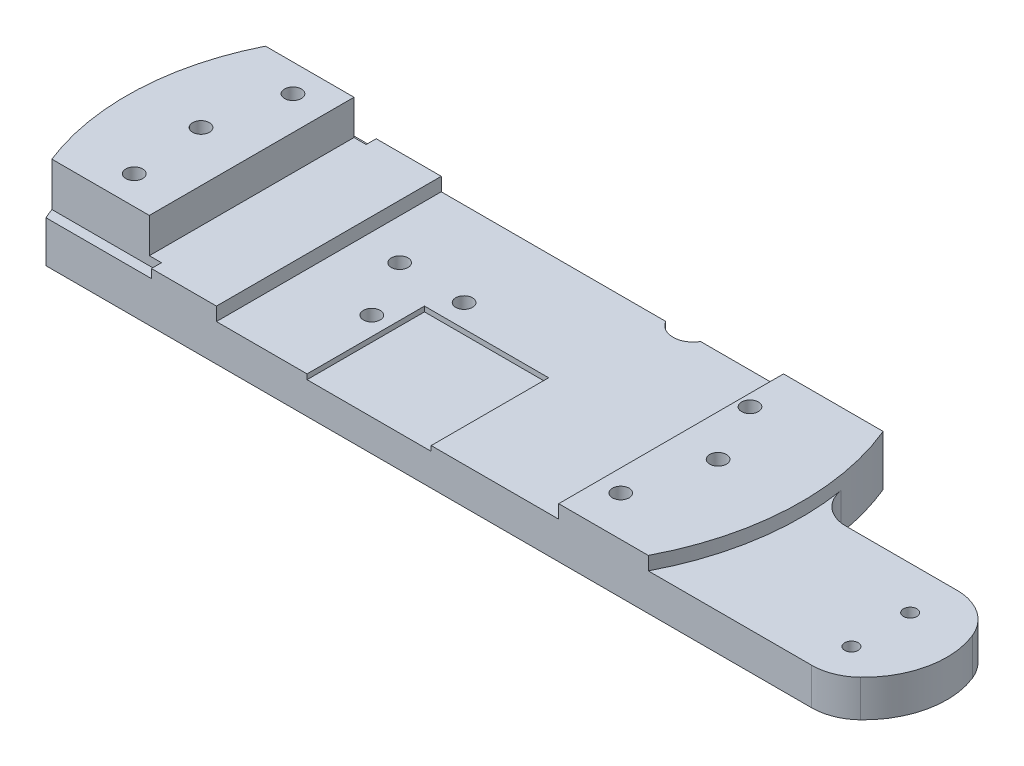
SolidWorks part; units mm, degrees
ref_plane "Front Plane" through (0, 0, 0) normal (0, 0, 1) x (1, 0, 0)
ref_plane "Top Plane" through (0, 0, 0) normal (0, 1, 0) x (1, 0, 0)
ref_plane "Right Plane" through (0, 0, 0) normal (1, 0, 0) x (0, 0, -1)
sketch "Sketch1" plane through (0, 0, 0) normal (0, 1, 0) x (1, 0, 0)
  line L1 (-97.5, -33.5) -> (97.5, -33.5)
  line L2 (-97.5, -33.5) -> (-97.5, 33.5)
  line L3 (-97.5, 33.5) -> (97.5, 33.5)
  line L4 (97.5, -33.5) -> (97.5, 33.5)
  line L5 (-97.5, -33.5) -> (97.5, 33.5) construction
  line L6 (-97.5, 33.5) -> (97.5, -33.5) construction
  point P0 (0, 0)
  dimension "D1" = 67
  dimension "D2" = 195
extrude "Boss-Extrude1" add sketch "Sketch1" along normal blind 25.4
sketch "Sketch2" plane through (0, 0, 0) normal (0, -1, 0) x (1, 0, 0)
  line L0 (-97.5, -33.5) -> (-97.5, 33.5) construction
  line L1 (97.5, 33.5) -> (97.5, -33.5) construction
  line L2 (97.5, 33.5) -> (88.5, 33.5)
  line L3 (-97.5, 33.5) -> (97.5, 33.5) construction
  line L4 (97.5, -33.5) -> (91.5, -33.5)
  line L5 (97.5, -33.5) -> (-97.5, -33.5) construction
  line L6 (-97.5, 33.5) -> (-91, 33.5)
  line L7 (-97.5, -33.5) -> (-88, -33.5)
  circle A0 centre (18.0922, -3.2198) radius 79.4078
  circle A1 centre (-22.6589, 2.9929) radius 74.8411
  line M7 (97.5, -33.5) -> (97.5, 33.5)
  line M8 (97.5, 33.5) -> (-97.5, 33.5)
  line M9 (-97.5, 33.5) -> (-97.5, -33.5)
  line M10 (-97.5, -33.5) -> (97.5, -33.5)
  dimension "D1" = 9
  dimension "D2" = 6
  dimension "D3" = 6.5
  dimension "D4" = 9.5
extrude "Cut-Extrude1" cut sketch "Sketch2" against normal through all contours A0 M7 M8 | A0 M10 M7 | A1 M9 M10 | A1 M8 M9
sketch "Sketch3" plane through (0, 0, 33.5) normal (0, 0, -1) x (-1, 0, 0)
  line L0 (97.5, 25.4) -> (63.2, 25.4)
  line L2 (63.2, 25.4) -> (63.2, 15)
  line L3 (63.2, 15) -> (40.2, 15)
  line L4 (40.2, 15) -> (40.2, 11)
  line L5 (40.2, 11) -> (-61.8, 11)
  line L6 (-91.5, 25.4) -> (88, 25.4) construction
  line L10 (97.5, 0) -> (97.5, 25.4) construction
  line L11 (-61.8, 11) -> (-61.8, 15)
  line L12 (-61.8, 15) -> (-97.5, 15)
  line L13 (-97.5, 25.4) -> (-97.5, 0) construction
  line L14 (-97.5, 15) -> (-97.5, 25.4)
  line L15 (-97.5, 25.4) -> (63.2, 25.4)
  line M13 (-88.5, 0) -> (-88.5, 25.4)
  line M14 (-88.5, 25.4) -> (91, 25.4)
  dimension "D1" = 10.4
  dimension "D2" = 34.3
  dimension "D3" = 23
  dimension "D4" = 4
  dimension "D5" = 102
extrude "Cut-Extrude2" cut sketch "Sketch3" along normal through all contours L11 L12 L2 L3 L4 L5 M13 M14
sketch "Sketch4" plane through (0, 25.4, 0) normal (0, 1, 0) x (1, 0, 0)
  line L0 (-59.5873, 33.5) -> (-59.5873, 30.5)
  line L1 (-63.2, 33.5) -> (-88, 33.5) construction
  line L2 (-59.5873, 30.5) -> (-89.5873, 30.5)
  line L3 (-59.5873, -33.5) -> (-59.5873, -30.5)
  line L4 (-91, -33.5) -> (-63.2, -33.5) construction
  line L5 (-59.5873, -30.5) -> (-92.2617, -30.5)
  line L6 (-59.5873, 33.5) -> (-63.2, 33.5)
  line L7 (-59.5873, -33.5) -> (-63.2, -33.5)
  arc A0 (-88, 33.5) -> (-91, -33.5) centre (-22.6589, -2.9929) ccw construction
  line M5 (-91, -33.5) -> (-63.2, -33.5)
  line M6 (-63.2, -33.5) -> (-63.2, 33.5)
  line M7 (-63.2, 33.5) -> (-88, 33.5)
  arc M8 (-88, 33.5) -> (-91, -33.5) centre (-22.6589, -2.9929) ccw
  dimension "D1" = 3
  dimension "D2" = 3
  dimension "D3" = 30
extrude "Cut-Extrude3" cut sketch "Sketch4" against normal blind 13 contours L2 M6 M7 M8 | L0 L6 L2 M6 | L5 M6 M8 M5 | L7 L3 L5 M6
sketch "Sketch6" plane through (0, 0, 0) normal (0, -1, 0) x (1, 0, 0)
  line L0 (-63.2, -33.5) -> (-97.5, -33.5)
  line L1 (91.5, -33.5) -> (-88, -33.5) construction
  line L2 (-63.2, -33.5) -> (-63.2, 33.5)
  line L3 (-91, 33.5) -> (88.5, 33.5) construction
  line L4 (-63.2, -9) -> (-28.1, -9) construction
  line L5 (-63.2, 8.7) -> (-18.7, 8.7) construction
  line L6 (-63.2, -8.3) -> (-8.2, -8.3) construction
  line L8 (91.5, -33.5) -> (-88, -33.5) construction
  line L9 (-97.5, -33.5) -> (-97.5, 33.5)
  line L10 (-97.5, 33.5) -> (-63.2, 33.5)
  circle A0 centre (-28.1, -9) radius 2.5
  circle A1 centre (-18.7, 8.7) radius 2.5
  circle A2 centre (74.1, -1.7) radius 2.5
  circle A3 centre (68.3, 21.5) radius 2.5
  circle A4 centre (65.3, -20) radius 2.5
  circle A5 centre (-8.2, -8.3) radius 2.5
  circle A6 centre (-76.2, 22) radius 2.5
  circle A7 centre (-78.2, 0.1) radius 2.5
  circle A8 centre (-73.2, -22.3) radius 2.5
  arc A10 (-91, 33.5) -> (-88, -33.5) centre (-22.6589, 2.9929) ccw construction
  dimension "D2" = 5
  dimension "D3" = 35.1
  dimension "D4" = 34.3
  dimension "D5" = 44.5
  dimension "D6" = 24.5
  dimension "D7" = 55
  dimension "D8" = 42.2
  dimension "D9" = 137.3
  dimension "D10" = 128.5
  dimension "D11" = 131.5
  dimension "D12" = 10
  dimension "D13" = 15
  dimension "D14" = 13
  dimension "D15" = 11.2
  dimension "D16" = 33.6
  dimension "D17" = 55.5
  dimension "D18" = 31.8
  dimension "D19" = 55
  dimension "D20" = 13.5
  dimension "D21" = 25.2
extrude "Cut-Extrude4" cut sketch "Sketch6" against normal through all contours A0 | A5 | A1 | A6 | A7 | A8 | A4 | A2 | A3
sketch "Sketch7" plane through (0, 11, 0) normal (0, 1, 0) x (1, 0, 0)
  line L1 (-13.2, 1.5) -> (23.8, 1.5)
  line L2 (-13.2, 1.5) -> (-13.2, -33.5)
  line L3 (-13.2, -33.5) -> (23.8, -33.5)
  line L4 (23.8, 1.5) -> (23.8, -33.5)
  line L8 (-63.2, 30.5) -> (-63.2, -30.5) construction
  line L9 (-63.2, 30.5) -> (-63.2, -30.5) construction
  line L10 (-40.2, -33.5) -> (61.8, -33.5) construction
  dimension "D1" = 50
  dimension "D2" = 87
  dimension "D3" = 35
extrude "Cut-Extrude5" cut sketch "Sketch7" against normal blind 1.5
sketch "Sketch8" plane through (0, 25.4, 0) normal (0, 1, 0) x (1, 0, 0)
  line L0 (-59.5873, -33.5) -> (-97.5, -33.5)
  line L1 (-97.5, -33.5) -> (-97.5, 33.5)
  line L3 (-97.5, 33.5) -> (31.9, 33.5)
  line L6 (31.9, 36.5) -> (31.9, 30.5)
  line L7 (31.9, 33.5) -> (37.0962, 33.5)
  line L10 (-59.5873, 33.5) -> (-88, 33.5) construction
  line L11 (-40.2, 33.5) -> (61.8, 33.5) construction
  circle A1 centre (31.9, 36.5) radius 6
  arc A2 (-89.5873, 30.5) -> (-92.2617, -30.5) centre (-22.6589, -2.9929) ccw construction
  dimension "D1" = 12
  dimension "D2" = 129.4
extrude "Cut-Extrude6" cut sketch "Sketch8" against normal blind 18.5 contours L6 A1 L7 | L3 A1 L6
sketch "Sketch9" plane through (0, 0, 0) normal (0, -1, 0) x (1, 0, 0)
  line L0 (88.5, 33.5) -> (137.2004, 33.5)
  line L1 (139.5727, -7.5) -> (97.3846, -7.5)
  arc A0 (153.4738, 1.8643) -> (147.5429, 29.3643) centre (130.3054, 11.2571) ccw
  arc A1 (91.5, -33.5) -> (88.5, 33.5) centre (18.0922, -3.2198) ccw construction
  arc A2 (143.371, -10.0569) -> (147.5429, 29.3643) centre (130.3054, 11.2571) ccw construction
  arc A3 (147.5429, 29.3643) -> (137.2004, 33.5) centre (137.2004, 18.5) ccw
  arc A4 (147.5429, 29.3643) -> (138.7351, 33.4213) centre (137.2004, 18.5) ccw construction
  arc A5 (139.5727, -7.5) -> (153.4738, 1.8643) centre (139.5727, 7.5) ccw
  circle A6 centre (114.5043, -27.5) radius 16 construction
  circle A7 centre (104.9862, 59.4808) radius 16 construction
  circle A8 centre (114.5043, -27.5) radius 20 construction
  arc A9 (97.3846, -7.5) -> (88.5, 33.5) centre (18.0922, -3.2198) ccw
  circle A10 centre (138.3, 5.25) radius 2
  circle A11 centre (138.3, 22.75) radius 2
  circle A12 centre (138.3, 22.75) radius 2 construction
  circle A13 centre (138.3, 5.25) radius 2 construction
  dimension "D1" = 4
extrude "Boss-Extrude2" add sketch "Sketch9" against normal up to surface (11 mm away) up to face at (-5.7, 11, -8.3)
fillet "Fillet1" radius 10 1 edges at (97.3846, 5.5, -7.5)
